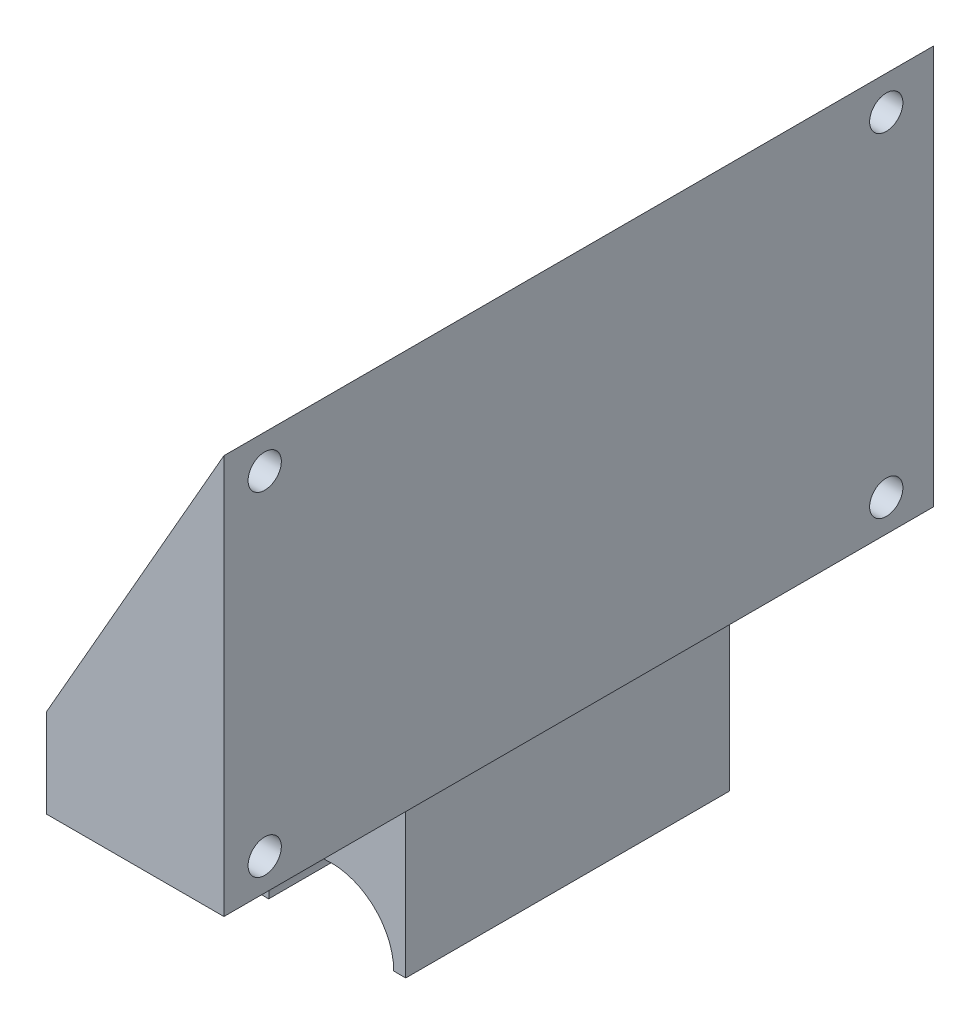
SolidWorks part; units mm, degrees
ref_plane "Front" through (0, 0, 0) normal (0, 0, 1) x (1, 0, 0)
ref_plane "Top" through (0, 0, 0) normal (0, 1, 0) x (1, 0, 0)
ref_plane "Right" through (0, 0, 0) normal (1, 0, 0) x (0, 0, -1)
sketch "Sketch1" plane through (0, 0, 0) normal (0, 0, 1) x (1, 0, 0)
  line L1 (0, 0) -> (25.4, 0)
  line L2 (0, 0) -> (0, 12.7)
  line L5 (25.4, 57.15) -> (0, 12.7)
  line L7 (25.4, 57.15) -> (25.4, 0)
  dimension "D1" = 12.7
  dimension "D2" = 57.15
  dimension "D3" = 25.4
extrude "Boss-Extrude1" add sketch "Sketch1" against normal blind 101.6
sketch "Sketch4" plane through (21.8096, 0, -29.4612) normal (0, -1, 0) x (-1, 0, 0)
  line L1 (-2.0029, -1.8387) -> (19.3331, -1.8387)
  line L2 (-2.0029, -1.8387) -> (-2.0029, 44.5163)
  line L3 (-2.0029, 44.5163) -> (19.3331, 44.5163)
  line L4 (19.3331, -1.8387) -> (19.3331, 44.5163)
  line L7 (-3.5904, 72.1388) -> (-3.5904, -29.4612) construction
  line L8 (21.8096, -29.4612) -> (-3.5904, -29.4612) construction
  dimension "D1" = 21.336
  dimension "D2" = 46.355
  dimension "D3" = 1.5875
  dimension "D4" = 27.6225
extrude "Boss-Extrude2" add sketch "Sketch4" along normal blind 22.225
sketch "Sketch7" plane through (0, 0, -73.9775) normal (0, 0, -1) x (-1, 0, 0)
  line L0 (-2.4765, -22.225) -> (-23.8125, -22.225) construction
  line L1 (-23.8125, -22.225) -> (-23.8125, 0) construction
  arc A0 (-22.098, -22.225) -> (-4.191, -22.225) centre (-13.1445, -22.225) cw
  dimension "D1" = 1.7145
extrude "Cut-Extrude5" cut sketch "Sketch7" against normal through all and the other way through all flip side to cut
sketch "Sketch8" plane through (25.4, 0, 0) normal (1, 0, 0) x (0, 0, -1)
  line L0 (0, 0) -> (0, 57.15) construction
  line L1 (101.6, 57.15) -> (0, 57.15) construction
  line L2 (101.6, 0) -> (0, 0) construction
  line L3 (101.6, 0) -> (101.6, 57.15) construction
  circle A0 centre (5.842, 52.324) radius 2.3812
  circle A1 centre (5.842, 4.572) radius 2.3813
  circle A2 centre (94.8379, 4.572) radius 2.3813
  circle A3 centre (94.8379, 52.324) radius 2.3813
  point P8 (0, 0)
  point P9 (0, 0)
  point P10 (0, 0)
  point P11 (0, 0)
  point P14 (0, 0)
  point P16 (10.8851, 59.8333)
  point P18 (0, 0)
  dimension "D1" = 4.7625
  dimension "D4" = 4.826
  dimension "D2" = 5.842
  dimension "D3" = 4.572
  dimension "D5" = 6.7621
extrude "Cut-Extrude6" cut sketch "Sketch8" against normal through all
